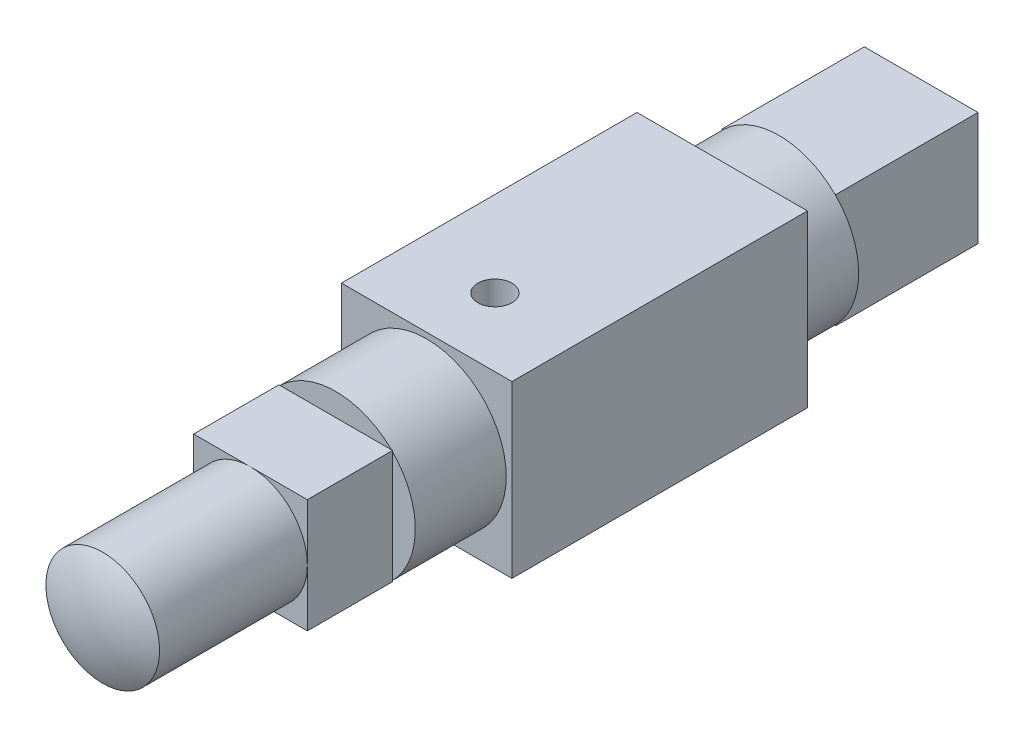
SolidWorks part; units mm, degrees
ref_plane "Front Plane" through (0, 0, 0) normal (0, 0, 1) x (1, 0, 0)
ref_plane "Top Plane" through (0, 0, 0) normal (0, 1, 0) x (1, 0, 0)
ref_plane "Right Plane" through (0, 0, 0) normal (1, 0, 0) x (0, 0, -1)
sketch "Sketch1" plane through (0, 0, 0) normal (0, 0, 1) x (1, 0, 0)
  line L1 (-7.5, -7.5) -> (7.5, -7.5)
  line L2 (-7.5, -7.5) -> (-7.5, 7.5)
  line L3 (-7.5, 7.5) -> (7.5, 7.5)
  line L4 (7.5, -7.5) -> (7.5, 7.5)
  line L5 (-7.5, -7.5) -> (7.5, 7.5) construction
  line L6 (-7.5, 7.5) -> (7.5, -7.5) construction
  point P0 (0, 0)
  dimension "D1" = 15
extrude "Boss-Extrude1" add sketch "Sketch1" along normal blind 26
sketch "Sketch2" plane through (0, 7.5, 0) normal (0, 1, 0) x (1, 0, 0)
  line L0 (7.5, -26) -> (-7.5, -26) construction
  line L1 (7.5, -26) -> (-7.5, -26)
  line L2 (0, -26) -> (0, -20)
  circle A0 centre (0, -20) radius 1.5
  dimension "D2" = 3
  dimension "D1" = 6
extrude "Cut-Extrude1" cut sketch "Sketch2" against normal through all
sketch "Sketch3" plane through (0, 0, 26) normal (0, 0, 1) x (1, 0, 0)
  circle A0 centre (0, 0) radius 7
  dimension "D1" = 14
extrude "Boss-Extrude2" add sketch "Sketch3" along normal blind 8
sketch "Sketch4" plane through (0, 0, 34) normal (0, 0, 1) x (1, 0, 0)
  line L1 (-5, -5) -> (5, -5)
  line L2 (-5, -5) -> (-5, 5)
  line L3 (-5, 5) -> (5, 5)
  line L4 (5, -5) -> (5, 5)
  line L5 (-5, -5) -> (5, 5) construction
  line L6 (-5, 5) -> (5, -5) construction
  point P0 (0, 0)
  dimension "D1" = 10
extrude "Boss-Extrude3" add sketch "Sketch4" along normal blind 7.5
sketch "Sketch5" plane through (0, 0, 41.5) normal (0, 0, 1) x (1, 0, 0)
  circle A0 centre (0, 0) radius 5
  dimension "D1" = 10
extrude "Boss-Extrude4" add sketch "Sketch5" along normal blind 13
sketch "Sketch6" plane through (0, 0, 0) normal (0, 1, 0) x (1, 0, 0)
  line L0 (-5, -54.5) -> (5, -54.5) construction
  line L1 (0, -54.5) -> (5, -54.5)
  line L3 (0, -54.5) -> (0, -55.7956)
  arc A0 (0, -55.7956) -> (5, -54.5) centre (0, -45.5) ccw
  dimension "D2" = 1.2956
  dimension "D3" = 10.2956
  dimension "D1" = 9
revolve "Revolve1" add sketch "Sketch6" angle 360 about L3
sketch "Sketch7" plane through (0, 0, 0) normal (0, 0, -1) x (-1, 0, 0)
  circle A0 centre (0, 0) radius 7
  dimension "D1" = 14
extrude "Boss-Extrude5" add sketch "Sketch7" along normal blind 5
sketch "Sketch8" plane through (0, 0, -5) normal (0, 0, -1) x (-1, 0, 0)
  line L1 (-5, -5) -> (5, -5)
  line L2 (-5, -5) -> (-5, 5)
  line L3 (-5, 5) -> (5, 5)
  line L4 (5, -5) -> (5, 5)
  line L5 (-5, -5) -> (5, 5) construction
  line L6 (-5, 5) -> (5, -5) construction
  point P0 (0, 0)
  dimension "D1" = 10
extrude "Boss-Extrude6" add sketch "Sketch8" along normal blind 12.5
